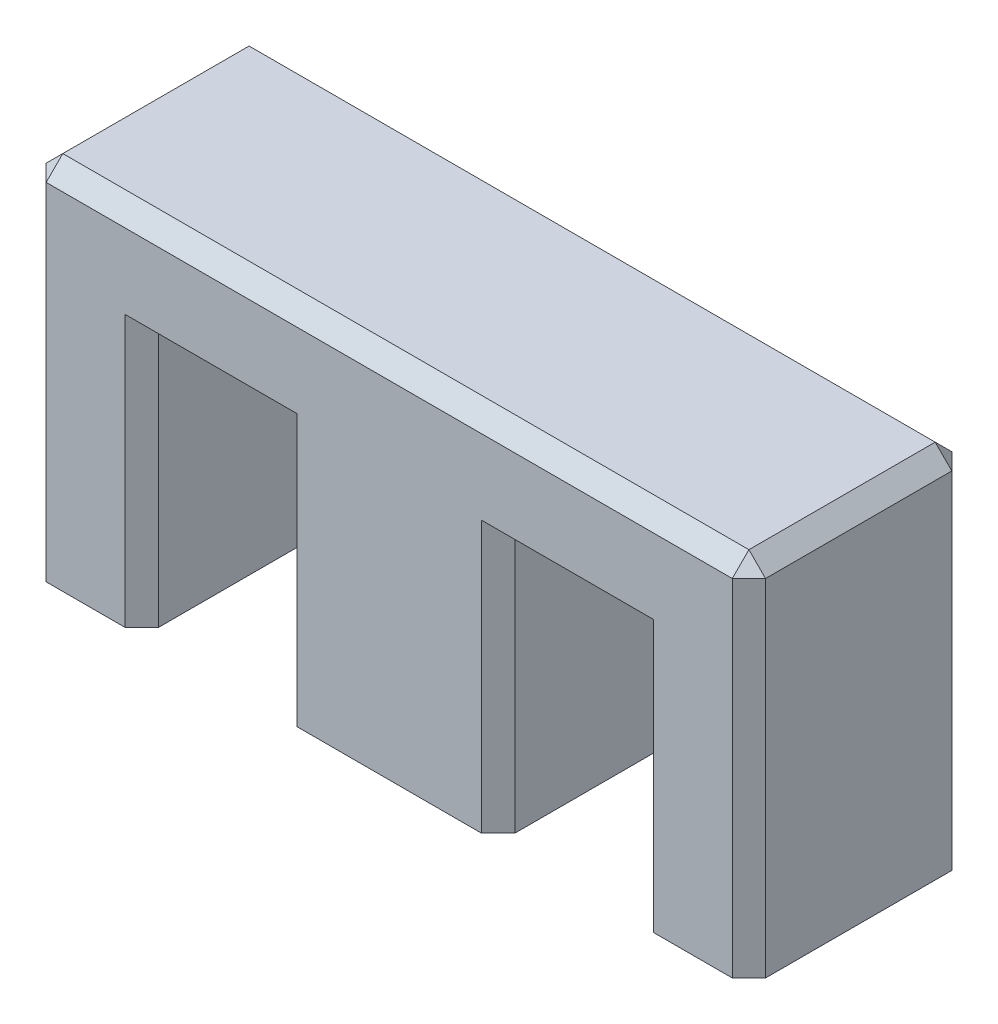
SolidWorks part; units mm, degrees
material "Ductile Iron"
ref_plane "Front Plane" through (0, 0, 0) normal (0, 0, 1) x (1, 0, 0)
ref_plane "Top Plane" through (0, 0, 0) normal (0, 1, 0) x (1, 0, 0)
ref_plane "Right Plane" through (0, 0, 0) normal (1, 0, 0) x (0, 0, -1)
sketch "Sketch1" plane through (0, 0, 0) normal (0, 0, 1) x (1, 0, 0)
  line L0 (0, 33.0544) -> (0, -29.4507) construction
  line L1 (43.25, 31.1735) -> (-43.25, 31.1735)
  line L2 (-43.25, 31.1735) -> (-43.25, -12.4265)
  line L3 (-43.25, -12.4265) -> (-29.75, -12.4265)
  line L4 (-29.75, -12.4265) -> (-29.75, 18.1735)
  line L5 (-29.75, 18.1735) -> (-13.1, 18.1735)
  line L6 (-13.1, 18.1735) -> (-13.1, -12.4265)
  line L7 (-13.1, -12.4265) -> (13.1, -12.4265)
  line L8 (13.1, 18.1735) -> (13.1, -12.4265)
  line L9 (29.75, 18.1735) -> (13.1, 18.1735)
  line L10 (29.75, -12.4265) -> (29.75, 18.1735)
  line L11 (43.25, -12.4265) -> (29.75, -12.4265)
  line L12 (43.25, 31.1735) -> (43.25, -12.4265)
  point P12 (0, -12.4265)
  point P13 (0, 31.1735)
  dimension "D1" = 86.5
  dimension "D2" = 43.6
  dimension "D3" = 26.2
  dimension "D4" = 13
  dimension "D5" = 13.5
extrude "Boss-Extrude1" add sketch "Sketch1" along normal mid plane 26.4
chamfer "Chamfer1" distance 2 angle 45 20 edges at (43.25, 31.1735, 0) (43.25, 9.3735, 13.2) (0, 31.1735, 13.2) (-43.25, 9.3735, 13.2) (-43.25, 31.1735, 0) (-43.25, 9.3735, -13.2) (0, 31.1735, -13.2) (43.25, 9.3735, -13.2) (13.1, 2.8735, -13.2) (29.75, 2.8735, -13.2) (21.425, 18.1735, -13.2) (-29.75, 2.8735, -13.2) (-13.1, 2.8735, -13.2) (-21.425, 18.1735, -13.2) (29.75, 2.8735, 13.2) (13.1, 2.8735, 13.2) (21.425, 18.1735, 13.2) (-29.75, 2.8735, 13.2) (-13.1, 2.8735, 13.2) (-21.425, 18.1735, 13.2)
